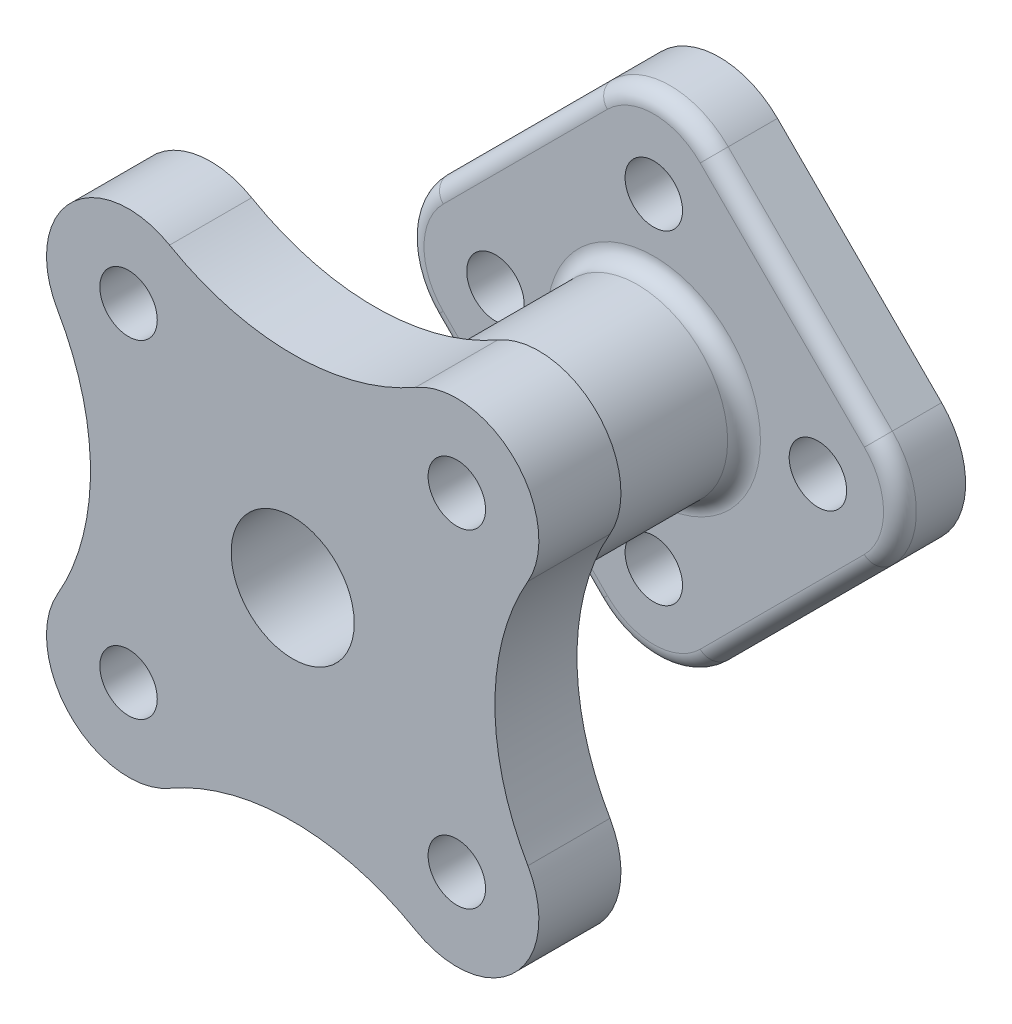
SolidWorks part; units mm, degrees
material "1060 합금"
ref_plane "정면" through (0, 0, 0) normal (0, 0, 1) x (1, 0, 0)
ref_plane "윗면" through (0, 0, 0) normal (0, 1, 0) x (1, 0, 0)
ref_plane "우측면" through (0, 0, 0) normal (1, 0, 0) x (0, 0, -1)
sketch "스케치1" plane through (0, 0, 0) normal (0, 0, 1) x (1, 0, 0)
  line L0 (-25.4, 0) -> (25.4, 0) construction
  line L5 (0, 25.4) -> (0, -25.4) construction
  arc A0 (-19.05, 36.3985) -> (-36.3985, 19.05) centre (-25.4, 25.4) ccw
  arc A1 (-36.3985, 19.05) -> (-36.3985, -19.05) centre (-69.3941, 0) cw
  arc A2 (-19.05, 36.3985) -> (19.05, 36.3985) centre (0, 69.3941) ccw
  arc A3 (19.05, 36.3985) -> (36.3985, 19.05) centre (25.4, 25.4) cw
  arc A4 (36.3985, 19.05) -> (36.3985, -19.05) centre (69.3941, 0) ccw
  arc A5 (19.05, -36.3985) -> (36.3985, -19.05) centre (25.4, -25.4) ccw
  arc A6 (-19.05, -36.3985) -> (19.05, -36.3985) centre (0, -69.3941) cw
  arc A7 (-19.05, -36.3985) -> (-36.3985, -19.05) centre (-25.4, -25.4) cw
  point P3 (0, 0)
  point P9 (0, 0)
  dimension "D2" = 12.7
  dimension "D3" = 38.1
  dimension "D1" = 50.8
extrude "보스-돌출1" add sketch "스케치1" against normal blind 12.7
sketch "스케치2" plane through (0, 0, -12.7) normal (0, 0, -1) x (-1, 0, 0)
  circle A0 centre (0, 0) radius 13.97
  dimension "D1" = 27.94
extrude "보스-돌출2" add sketch "스케치2" along normal blind 43.18
sketch "스케치4" plane through (0, 0, -55.88) normal (0, 0, -1) x (-1, 0, 0)
  line L0 (-34.3803, 8.9803) -> (-8.9803, 34.3803)
  line L1 (-34.3803, -8.9803) -> (-8.9803, -34.3803)
  line L2 (8.9803, 34.3803) -> (34.3803, 8.9803)
  line L3 (8.9803, -34.3803) -> (34.3803, -8.9803)
  line L4 (-43.3605, 0) -> (43.3605, 0) construction
  line L5 (0, 43.3605) -> (0, -43.3605) construction
  arc A0 (34.3803, 8.9803) -> (34.3803, -8.9803) centre (25.4, 0) cw
  arc A1 (-8.9803, -34.3803) -> (8.9803, -34.3803) centre (0, -25.4) ccw
  arc A2 (-34.3803, -8.9803) -> (-34.3803, 8.9803) centre (-25.4, 0) cw
  arc A3 (-8.9803, 34.3803) -> (8.9803, 34.3803) centre (0, 25.4) cw
  point P1 (0, 0)
  dimension "D1" = 12.7
  dimension "D2" = 50.8
extrude "보스-돌출3" add sketch "스케치4" along normal blind 10.16
sketch "스케치5" plane through (0, 0, 0) normal (0, 0, 1) x (1, 0, 0)
  circle A0 centre (0, 0) radius 9.525
  dimension "D1" = 19.05
extrude "컷-돌출1" cut sketch "스케치5" against normal through all
sketch "스케치6" plane through (0, 0, 0) normal (0, 0, 1) x (1, 0, 0)
  circle A0 centre (-25.4, 25.4) radius 4.445
  circle A3 centre (-25.4, -25.4) radius 4.445
  circle A4 centre (25.4, -25.4) radius 4.445
  circle A5 centre (25.4, 25.4) radius 4.445
  dimension "D1" = 8.89
extrude "컷-돌출2" cut sketch "스케치6" against normal up to next
sketch "스케치7" plane through (0, 0, -55.88) normal (0, 0, 1) x (1, 0, 0)
  circle A0 centre (0, 24.8239) radius 4.445
  circle A1 centre (25.4, 0) radius 4.445
  circle A2 centre (0, -25.4) radius 4.445
  circle A3 centre (-24.5014, 0) radius 4.445
extrude "컷-돌출3" cut sketch "스케치7" against normal up to next
fillet "필렛1" radius 2.54 9 edges at (0, 38.1, -55.88) (-21.6803, 21.6803, -55.88) (-38.1, 0, -55.88) (-21.6803, -21.6803, -55.88) (0, -38.1, -55.88) (21.6803, -21.6803, -55.88) (38.1, 0, -55.88) (-13.97, 0, -55.88) (21.6803, 21.6803, -55.88)
